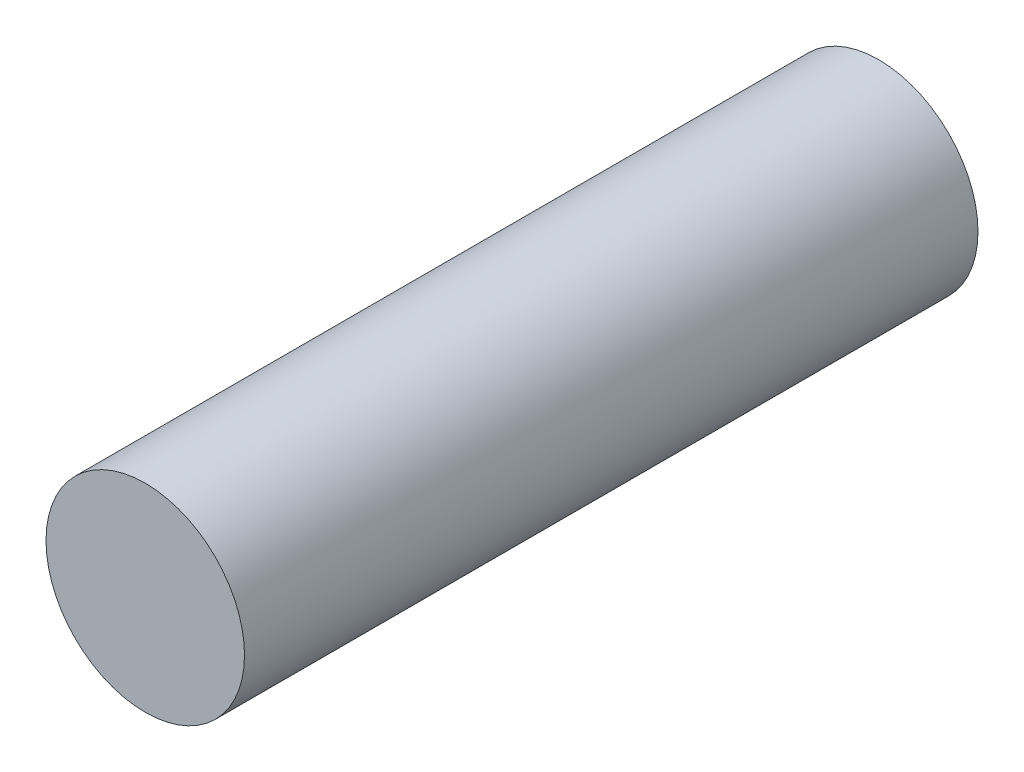
SolidWorks part; units mm, degrees
material "3003 Alloy"
ref_plane "Front Plane" through (0, 0, 0) normal (0, 0, 1) x (1, 0, 0)
ref_plane "Top Plane" through (0, 0, 0) normal (0, 1, 0) x (1, 0, 0)
ref_plane "Right Plane" through (0, 0, 0) normal (1, 0, 0) x (0, 0, -1)
sketch "Sketch1" plane through (0, 0, 0) normal (0, 0, 1) x (1, 0, 0)
  circle A0 centre (0, 0) radius 2
  dimension "D1" = 4
extrude "Boss-Extrude1" add sketch "Sketch1" along normal blind 14.78
